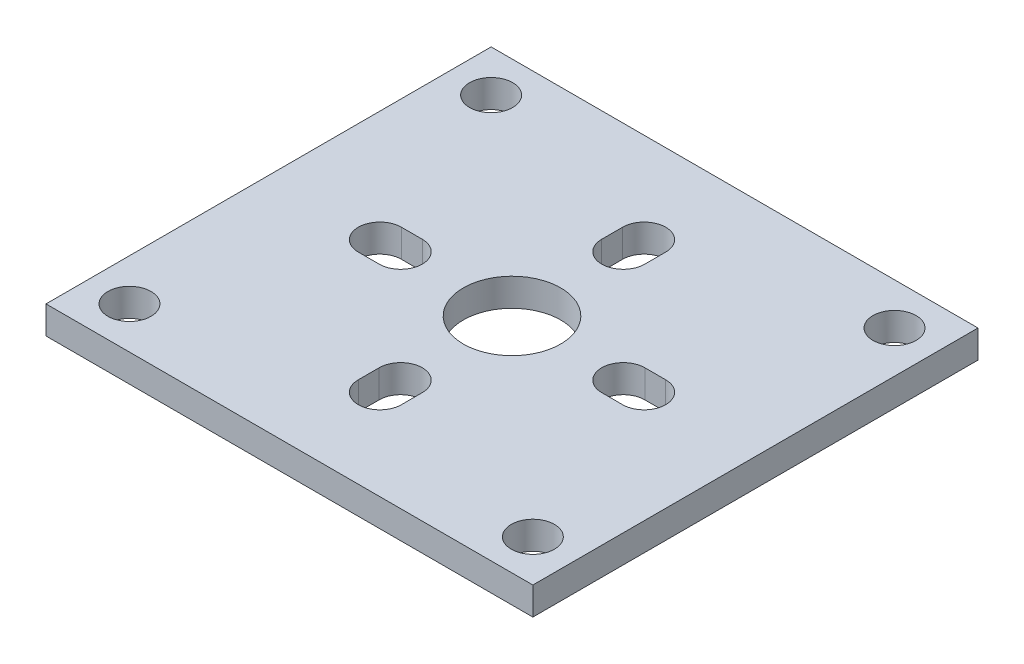
SolidWorks part; units mm, degrees
ref_plane "前视基准面" through (0, 0, 0) normal (0, 0, 1) x (1, 0, 0)
ref_plane "上视基准面" through (0, 0, 0) normal (0, 1, 0) x (1, 0, 0)
ref_plane "右视基准面" through (0, 0, 0) normal (1, 0, 0) x (0, 0, -1)
other "Configuration Table"
sketch "草图1" plane through (0, 0, 0) normal (0, 1, 0) x (1, 0, 0)
  line L0 (-1.55, 9.5) -> (-1.55, 8)
  line L1 (17.5, -16) -> (-17.5, -16)
  line L2 (17.5, -16) -> (17.5, 16)
  line L3 (17.5, 16) -> (-17.5, 16)
  line L4 (-17.5, -16) -> (-17.5, 16)
  line L5 (17.5, -16) -> (-17.5, 16) construction
  line L6 (17.5, 16) -> (-17.5, -16) construction
  line L7 (1.55, 9.5) -> (1.55, 8)
  line L14 (6.4528, 0) -> (0, 0) construction
  line L15 (0, 0) -> (4.4177, 4.4177) construction
  line L16 (1.55, -9.5) -> (1.55, -8)
  line L17 (-1.55, -9.5) -> (-1.55, -8)
  line L18 (-9.5, -1.55) -> (-8, -1.55)
  line L19 (-9.5, 1.55) -> (-8, 1.55)
  line L20 (9.5, 1.55) -> (8, 1.55)
  line L21 (9.5, -1.55) -> (8, -1.55)
  circle A0 centre (0, 0) radius 8 construction
  circle A1 centre (0, 0) radius 9.5 construction
  arc A2 (-1.55, 8) -> (1.55, 8) centre (0, 8) ccw
  arc A4 (1.55, 9.5) -> (-1.55, 9.5) centre (0, 9.5) ccw
  circle A11 centre (0, 0) radius 3.5
  arc A12 (1.55, -9.5) -> (-1.55, -9.5) centre (0, -9.5) cw
  arc A13 (-1.55, -8) -> (1.55, -8) centre (0, -8) cw
  arc A14 (-8, -1.55) -> (-8, 1.55) centre (-8, 0) ccw
  arc A15 (-9.5, 1.55) -> (-9.5, -1.55) centre (-9.5, 0) ccw
  arc A16 (9.5, 1.55) -> (9.5, -1.55) centre (9.5, 0) cw
  arc A17 (8, -1.55) -> (8, 1.55) centre (8, 0) cw
  point P0 (0, 0)
  dimension "D2" = 16
  dimension "D3" = 19
  dimension "D4" = 1.55
  dimension "D5" = 7
  dimension "D1" = 35
  dimension "D6" = 32
  dimension "D7" = 45
extrude "凸台-拉伸1" add sketch "草图1" along normal blind 2
sketch "草图2" plane through (0, 2, 0) normal (0, 1, 0) x (1, 0, 0)
  line L0 (0, 0) -> (0, 16.2595) construction
  line L1 (-14.5, 13) -> (-14.5, -13) construction
  line L2 (0, 0) -> (-14.5, 0) construction
  line L3 (14.5, 13) -> (14.5, -13) construction
  line L4 (-17.5, 16) -> (-17.5, -16) construction
  circle A0 centre (-14.5, 13) radius 1.55
  circle A1 centre (-14.5, -13) radius 1.55
  circle A2 centre (14.5, -13) radius 1.55
  circle A3 centre (14.5, 13) radius 1.55
  dimension "D1" = 3.1
  dimension "D2" = 26
  dimension "D3" = 3
extrude "切除-拉伸1" cut sketch "草图2" against normal blind 10
